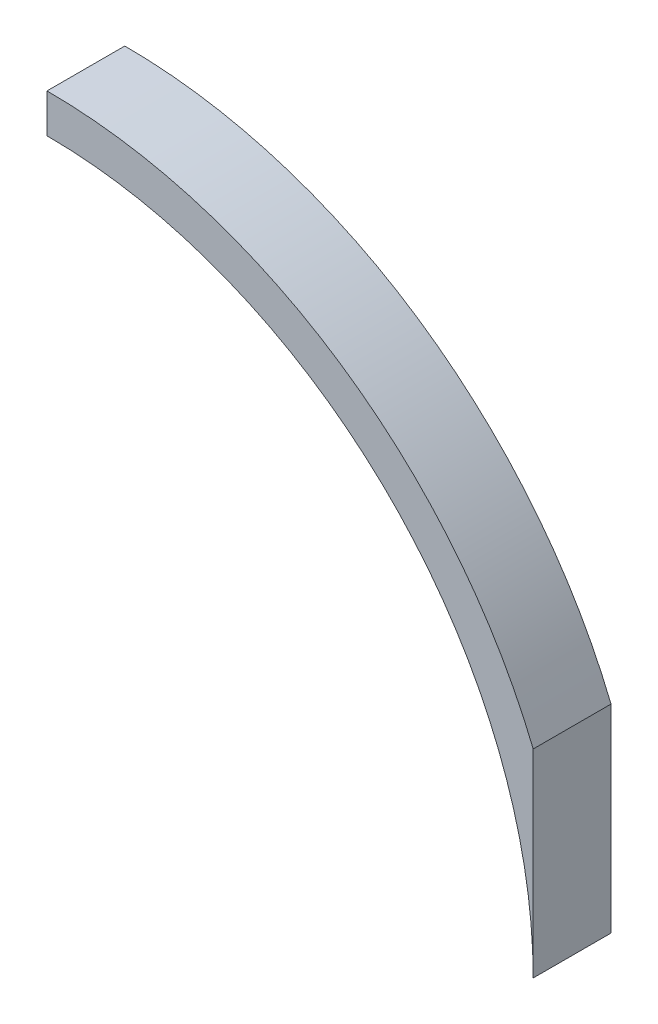
SolidWorks part; units mm, degrees
ref_plane "Plan de face" through (0, 0, 0) normal (0, 0, 1) x (1, 0, 0)
ref_plane "Plan de dessus" through (0, 0, 0) normal (0, 1, 0) x (1, 0, 0)
ref_plane "Plan de droite" through (0, 0, 0) normal (1, 0, 0) x (0, 0, -1)
sketch "Esquisse1" plane through (0, 0, 0) normal (0, 0, 1) x (1, 0, 0)
  line L0 (125, 0) -> (135, 0)
  line L1 (125, 0) -> (0, 0) construction
  line L2 (0, 125) -> (0, 135) construction
  line L3 (0, 0) -> (0, 125) construction
  line L4 (0, 125) -> (0, 135)
  arc A0 (125, 0) -> (0, 125) centre (0, 0) ccw
  arc A1 (135, 0) -> (0, 135) centre (0, 0) ccw
  dimension "D1" = 10
  dimension "D2" = 90
  dimension "D3" = 125
extrude "Boss.-Extru.1" add sketch "Esquisse1" along normal blind 20
sketch "Esquisse2" plane through (0, 0, 20) normal (0, 0, 1) x (1, 0, 0)
  line L0 (0, 0) -> (125, 0) construction
  line L1 (125, 0) -> (135, 0) construction
  line L3 (125, 0) -> (135, 0)
  line L4 (125, 0) -> (125, 80)
  line L5 (125, 80) -> (135, 80)
  line L6 (135, 0) -> (135, 80)
  arc A0 (135, 0) -> (0, 135) centre (0, 0) ccw construction
  point P8 (0, 0)
  dimension "D1" = 80
  dimension "D2" = 10
extrude "Enlèv. mat.-Extru.1" cut sketch "Esquisse2" against normal through all both and the other way through all
